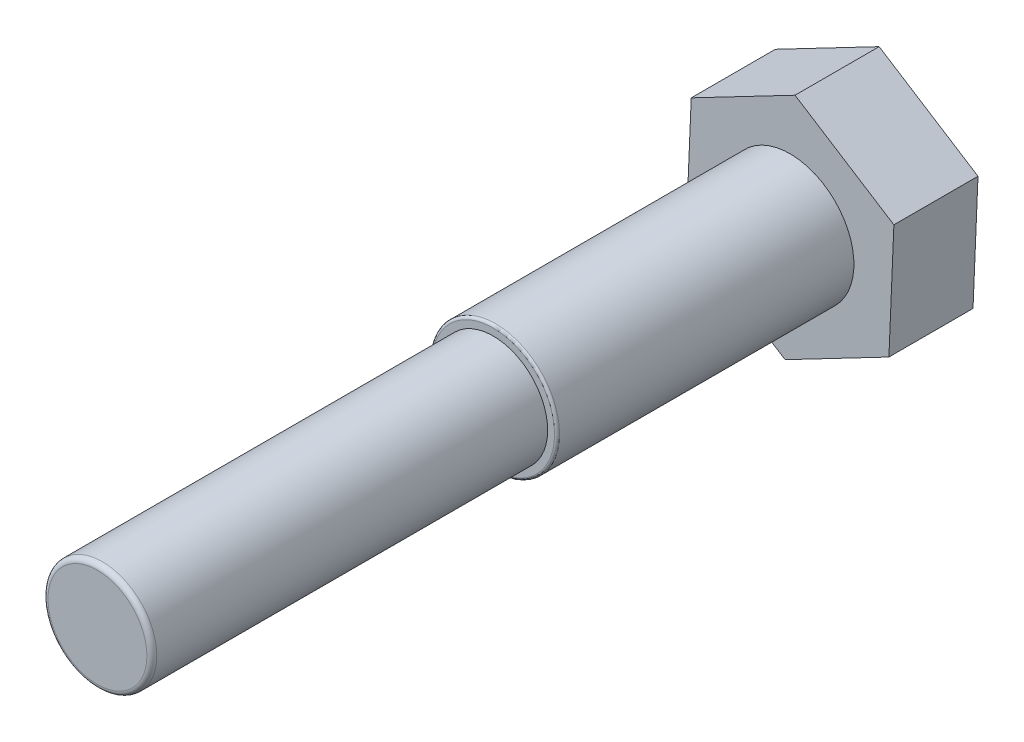
SolidWorks part; units mm, degrees
ref_plane "前视" through (0, 0, 0) normal (0, 0, 1) x (1, 0, 0)
ref_plane "上视" through (0, 0, 0) normal (0, 1, 0) x (1, 0, 0)
ref_plane "右视" through (0, 0, 0) normal (1, 0, 0) x (0, 0, -1)
sketch "草图1" plane through (0, 0, 0) normal (0, 0, 1) x (1, 0, 0)
  line L1 (20.9842, 10.9543) -> (1.0054, 23.65)
  line L2 (1.0054, 23.65) -> (-19.9788, 12.6957)
  line L3 (-19.9788, 12.6957) -> (-20.9842, -10.9543)
  line L4 (-20.9842, -10.9543) -> (-1.0054, -23.65)
  line L5 (-1.0054, -23.65) -> (19.9788, -12.6957)
  line L6 (19.9788, -12.6957) -> (20.9842, 10.9543)
  circle A0 centre (0, 0) radius 20.5 construction
  dimension "D1" = 47.3
  dimension "D2" = 41
extrude "基体-拉伸" add sketch "草图1" along normal blind 17
sketch "草图2" plane through (0, 0, 17) normal (0, 0, 1) x (1, 0, 0)
  circle A0 centre (0, 0) radius 12.9
  dimension "D1" = 25.8
extrude "凸台-拉伸1" add sketch "草图2" along normal blind 60
sketch "草图3" plane through (0, 0, 77) normal (0, 0, 1) x (1, 0, 0)
  circle A0 centre (0, 0) radius 11
  dimension "D1" = 22
extrude "凸台-拉伸2" add sketch "草图3" along normal blind 80
fillet "圆角2" radius 1 1 edges at (11, 0, 157)
fillet "圆角4" radius 0.5 1 edges at (12.9, 0, 77)
